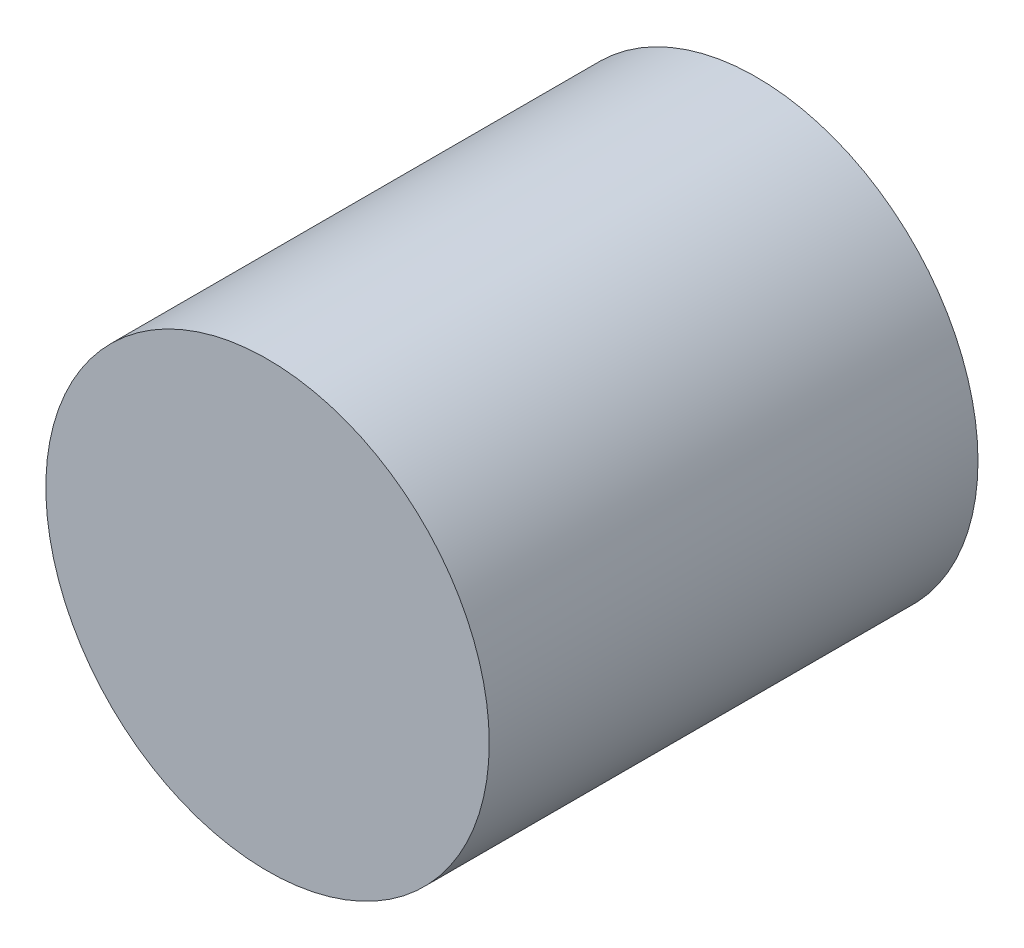
SolidWorks part; units mm, degrees
ref_plane "Front Plane" through (0, 0, 0) normal (0, 0, 1) x (1, 0, 0)
ref_plane "Top Plane" through (0, 0, 0) normal (0, 1, 0) x (1, 0, 0)
ref_plane "Right Plane" through (0, 0, 0) normal (1, 0, 0) x (0, 0, -1)
sketch "Sketch1" plane through (0, 0, 0) normal (0, 0, 1) x (1, 0, 0)
  circle A0 centre (7.125, -5.675) radius 9.5816
  dimension "D1" = 19.1632
extrude "Boss-Extrude1" add sketch "Sketch1" along normal blind 21.1226
